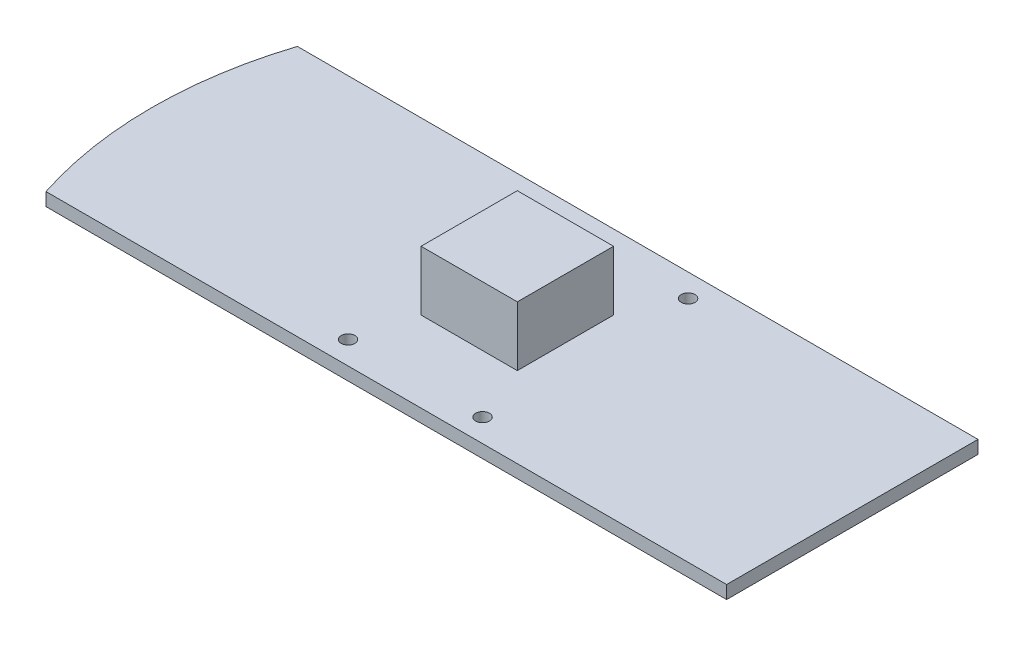
SolidWorks part; units mm, degrees
ref_plane "Front Plane" through (0, 0, 0) normal (0, 0, 1) x (1, 0, 0)
ref_plane "Top Plane" through (0, 0, 0) normal (0, 1, 0) x (1, 0, 0)
ref_plane "Right Plane" through (0, 0, 0) normal (1, 0, 0) x (0, 0, -1)
sketch "Sketch1" plane through (0, 0, 0) normal (0, 1, 0) x (1, 0, 0)
  line L1 (0, 0) -> (148.5, 0)
  line L2 (0, 0) -> (0, -54.85)
  line L3 (0, -54.85) -> (148.5, -54.85)
  line L4 (148.5, 0) -> (148.5, -54.85)
  arc A0 (0, 0) -> (0, -54.85) centre (84.6692, -27.425) ccw
  circle A1 centre (90.25, -49.85) radius 1.5
  circle A2 centre (60.9, -49.85) radius 1.5
  circle A3 centre (60.9, -5) radius 1.5
  circle A4 centre (90.25, -5) radius 1.5
  point P14 (65.6779, -7.6637)
  point P15 (0, 0)
  point P16 (0, 0)
  dimension "D3" = 89
  dimension "D1" = 54.85
  dimension "D2" = 148.5
  dimension "D4" = 58.25
  dimension "D5" = 29.35
  dimension "D6" = 5
  dimension "D7" = 29.35
  dimension "D8" = 58.25
  dimension "D9" = 5
extrude "Boss-Extrude1" add sketch "Sketch1" along normal blind 2.85 contours L4 L1 L2 L3 A4 A3 A2 A1 | L2 A0
sketch "Sketch2" plane through (0, 2.85, 0) normal (0, 1, 0) x (1, 0, 0)
  line L1 (64.2532, -37.2695) -> (85.2532, -37.2695)
  line L2 (64.2532, -37.2695) -> (64.2532, -16.2695)
  line L3 (64.2532, -16.2695) -> (85.2532, -16.2695)
  line L4 (85.2532, -37.2695) -> (85.2532, -16.2695)
  line L5 (64.2532, -37.2695) -> (85.2532, -16.2695) construction
  line L6 (64.2532, -16.2695) -> (85.2532, -37.2695) construction
  point P0 (74.7532, -26.7695)
  dimension "D1" = 21
extrude "Boss-Extrude2" add sketch "Sketch2" along normal blind 13
